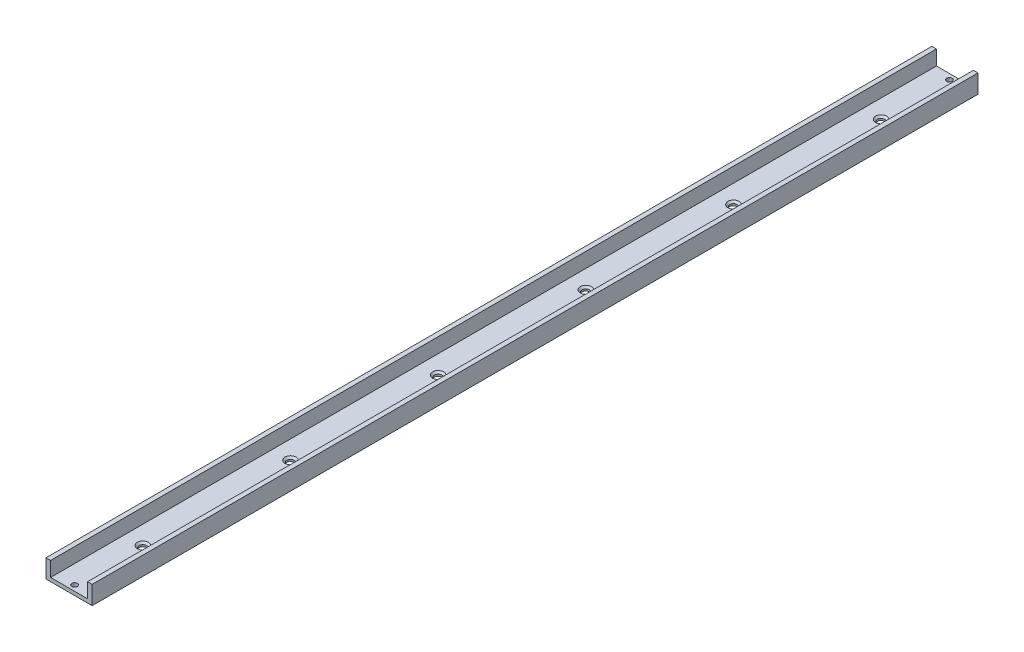
SolidWorks part; units mm, degrees
ref_plane "正面" through (0, 0, 0) normal (0, 0, 1) x (1, 0, 0)
ref_plane "平面" through (0, 0, 0) normal (0, 1, 0) x (1, 0, 0)
ref_plane "右側面" through (0, 0, 0) normal (1, 0, 0) x (0, 0, -1)
sketch "ｽｹｯﾁ1" plane through (0, 0, 0) normal (0, 0, 1) x (1, 0, 0)
  line L0 (0, 8) -> (-2.5, 8)
  line L1 (0, 0) -> (20, 0)
  line L2 (0, 0) -> (0, 8)
  line L4 (20, 0) -> (20, 8)
  line L5 (-2.5, 8) -> (-2.5, -2)
  line L6 (-2.5, -2) -> (22.5, -2)
  line L7 (22.5, -2) -> (22.5, 8)
  line L8 (22.5, 8) -> (20, 8)
  dimension "D1" = 20
  dimension "D2" = 25
  dimension "D3" = 2
  dimension "D4" = 10
extrude "ﾎﾞｽ - 押し出し1" add sketch "ｽｹｯﾁ1" along normal blind 480
sketch "ｽｹｯﾁ2" plane through (0, 0, 0) normal (0, 1, 0) x (1, 0, 0)
  line L0 (10, 0) -> (10, -480) construction
  line L1 (20, 0) -> (0, 0) construction
  line L2 (20, -480) -> (0, -480) construction
  line L3 (10, -482) -> (10, -472) construction
  circle A2 centre (10, -477) radius 5 construction
  circle A3 centre (10, -477) radius 1.5
  circle A4 centre (10, -440) radius 2
  circle A5 centre (10, -360) radius 2
  circle A6 centre (10, -280) radius 2
  circle A7 centre (10, -200) radius 2
  circle A8 centre (10, -120) radius 2
  circle A9 centre (10, -40) radius 2
  circle A10 centre (10, -3) radius 1.5
  dimension "D1" = 2
  dimension "D3" = 40
  dimension "D4" = 3
  dimension "D5" = 4
  dimension "D6" = 80
  dimension "D7" = 80
  dimension "D8" = 80
  dimension "D9" = 3
  dimension "D10" = 80
  dimension "D11" = 3
  dimension "D12" = 80
  dimension "D13" = 40
  dimension "D2" = 8
extrude "ｶｯﾄ - 押し出し1" cut sketch "ｽｹｯﾁ2" against normal through all
chamfer "面取り1" distance 1 angle 45 6 edges at (10, 0, 442) (10, 0, 42) (10, 0, 122) (10, 0, 202) (10, 0, 282) (10, 0, 362)
